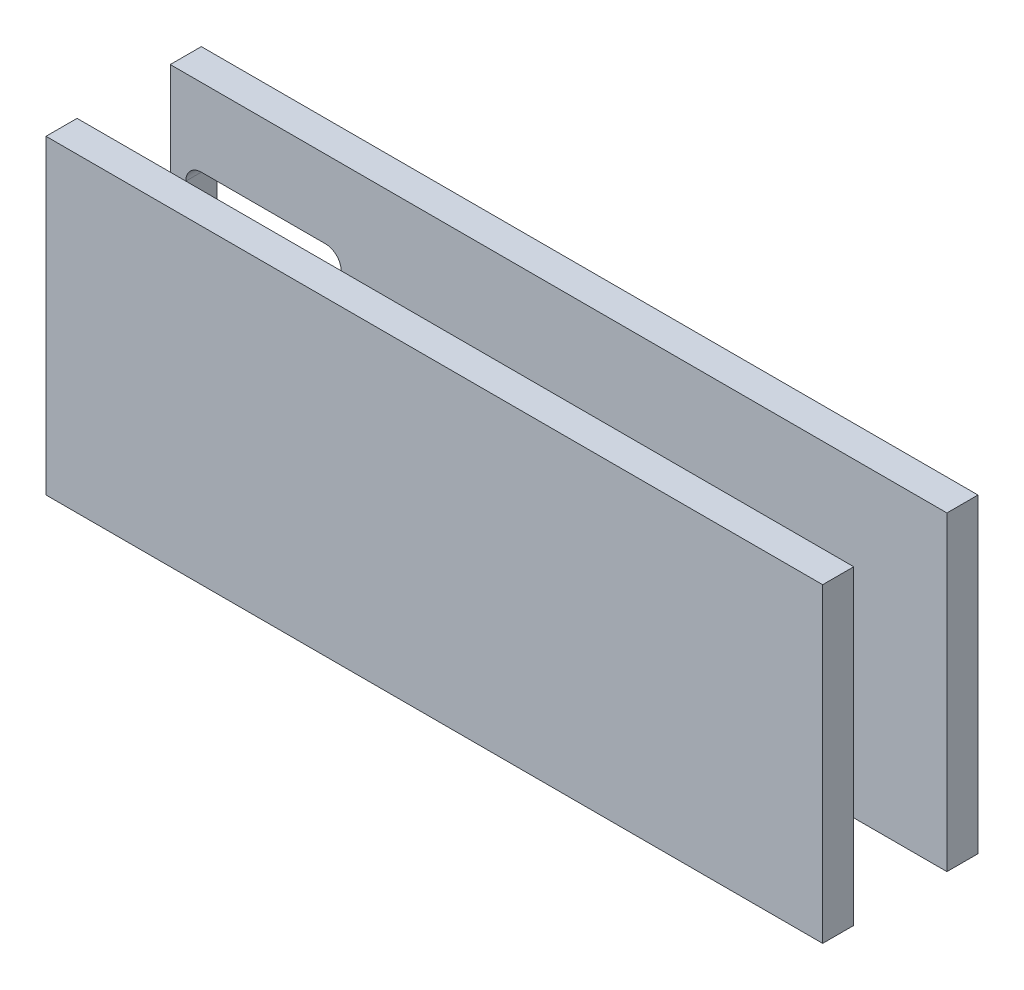
SolidWorks part; units mm, degrees
ref_plane "Front Plane" through (0, 0, 0) normal (0, 0, 1) x (1, 0, 0)
ref_plane "Top Plane" through (0, 0, 0) normal (0, 1, 0) x (1, 0, 0)
ref_plane "Right Plane" through (0, 0, 0) normal (1, 0, 0) x (0, 0, -1)
sketch "Sketch1" plane through (0, 0, 0) normal (0, 0, 1) x (1, 0, 0)
  line L1 (-125, 50) -> (125, 50)
  line L2 (-125, 50) -> (-125, -50)
  line L3 (-125, -50) -> (125, -50)
  line L4 (125, 50) -> (125, -50)
  line L5 (-125, 50) -> (125, -50) construction
  line L6 (-125, -50) -> (125, 50) construction
  point P0 (0, 0)
  dimension "D1" = 250
  dimension "D2" = 100
extrude "Boss-Extrude1" add sketch "Sketch1" along normal blind 10
sketch "Sketch2" plane through (0, 0, 10) normal (0, 0, 1) x (1, 0, 0)
  line L0 (125, -50) -> (125, 50) construction
  line L2 (125, 50) -> (-125, 50) construction
  circle A0 centre (75, 0) radius 5
  circle A1 centre (-25, 0) radius 5
  dimension "D2" = 10
  dimension "D3" = 10
  dimension "D4" = 50
  dimension "D5" = 100
  dimension "D1" = 50
extrude "Boss-Extrude2" add sketch "Sketch2" along normal blind 30
sketch "Sketch3" plane through (0, 0, 40) normal (0, 0, 1) x (1, 0, 0)
  line L1 (-125, 50) -> (125, 50)
  line L2 (-125, 50) -> (-125, -50)
  line L3 (-125, -50) -> (125, -50)
  line L4 (125, 50) -> (125, -50)
  line L5 (-125, 50) -> (125, -50) construction
  line L6 (-125, -50) -> (125, 50) construction
  point P0 (0, 0)
extrude "Boss-Extrude3" add sketch "Sketch3" along normal blind 10
sketch "Sketch5" plane through (0, 0, 0) normal (0, 0, -1) x (-1, 0, 0)
  line L1 (70, 25) -> (120, 25)
  line L2 (70, 25) -> (70, -25)
  line L3 (70, -25) -> (120, -25)
  line L4 (120, 25) -> (120, -25)
  line L5 (70, 25) -> (120, -25) construction
  line L6 (70, -25) -> (120, 25) construction
  line L7 (-125, 50) -> (125, 50) construction
  line L9 (125, 50) -> (125, -50) construction
  point P0 (95, 0)
  point P9 (125, -2.2384)
  dimension "D1" = 50
  dimension "D2" = 50
  dimension "D3" = 50
  dimension "D4" = 50
  dimension "D5" = 30
extrude "Cut-Extrude1" cut sketch "Sketch5" against normal blind 10
fillet "Fillet1" radius 5 4 edges at (-120, -25, 5) (-70, -25, 5) (-70, 25, 5) (-120, 25, 5)
